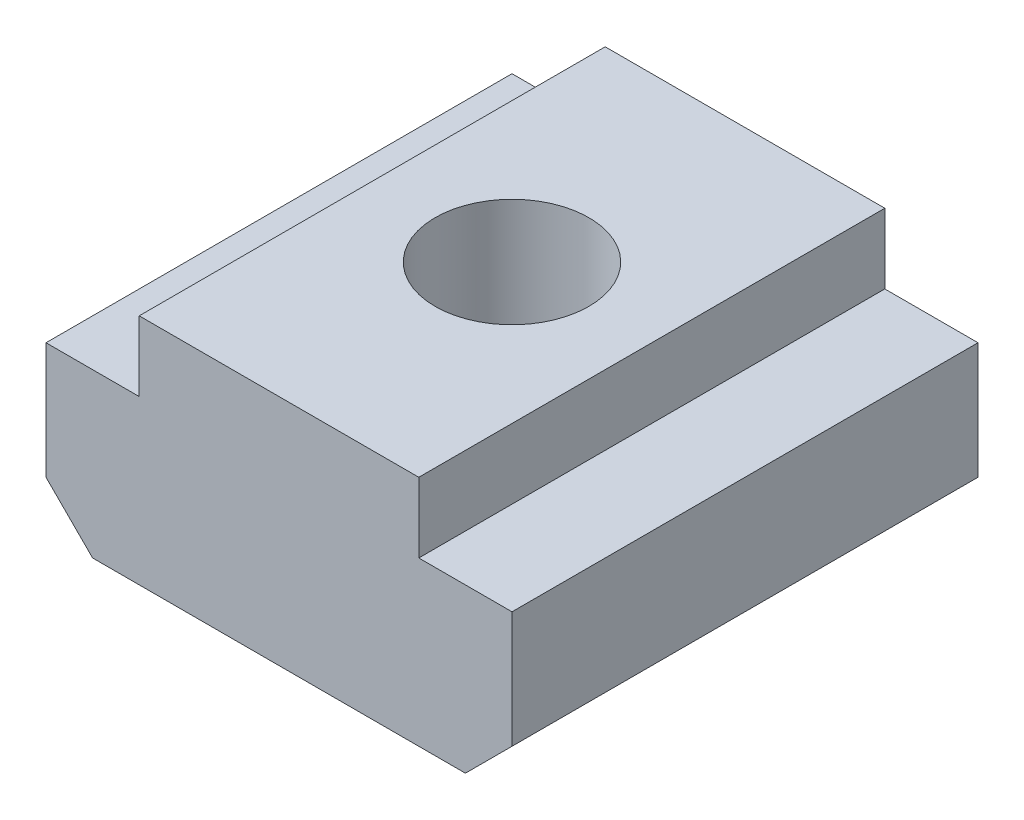
SolidWorks part; units mm, degrees
ref_plane "Front Plane" through (0, 0, 0) normal (0, 0, 1) x (1, 0, 0)
ref_plane "Top Plane" through (0, 0, 0) normal (0, 1, 0) x (1, 0, 0)
ref_plane "Right Plane" through (0, 0, 0) normal (1, 0, 0) x (0, 0, -1)
sketch "Sketch1" plane through (0, 0, 0) normal (0, 0, 1) x (1, 0, 0)
  line L0 (0, 0) -> (0, 46.9655) construction
  line L1 (-4, 0) -> (4, 0)
  line L2 (4, 0) -> (5, 1)
  line L3 (5, 1) -> (5, 3.5)
  line L4 (5, 3.5) -> (3, 3.5)
  line L5 (3, 3.5) -> (3, 5)
  line L6 (3, 5) -> (-3, 5)
  line L7 (-3, 5) -> (-3, 3.5)
  line L8 (-3, 3.5) -> (-5, 3.5)
  line L9 (-5, 3.5) -> (-5, 1)
  line L10 (-5, 1) -> (-4, 0)
  point P10 (0, 5)
  point P14 (-5, 2.25)
  dimension "D1" = 6
  dimension "D2" = 10
  dimension "D3" = 5
  dimension "D4" = 1.5
  dimension "D5" = 5
  dimension "D6" = 1
  dimension "D7" = 1
  dimension "D8" = 1
extrude "Boss-Extrude1" add sketch "Sketch1" along normal blind 10
sketch "Sketch2" plane through (0, 5, 0) normal (0, 1, 0) x (1, 0, 0)
  line L0 (-3, 0) -> (3, -10) construction
  point P4 (0, -5)
hole_wizard "M4x0.7 Tapped Hole1" positions "Sketch3" profile "Sketch4" tap size "M4x0.7" standard "ANSI Metric" end condition through all
sketch "Sketch3" plane through (0, 5, 0) normal (0, 1, 0) x (1, 0, 0)
  point P0 (0, -5)
sketch "Sketch4" plane through (0, 5, 5) normal (1, 0, 0) x (0, 0, 1)
  line L0 (0, 0) -> (0, 5)
  line L1 (0, 5) -> (1.65, 5)
  line L2 (1.65, 5) -> (1.65, 0)
  line L5 (1.65, 0) -> (0, 0)
  line L11 (0, -6.35) -> (0, 107.95) construction
  dimension "Thru Tap Drill Dia." = 3.3
  dimension "Thru Tap Drill Depth" = 5
cosmetic thread "Hole Thread1" parameters "D2"=4
